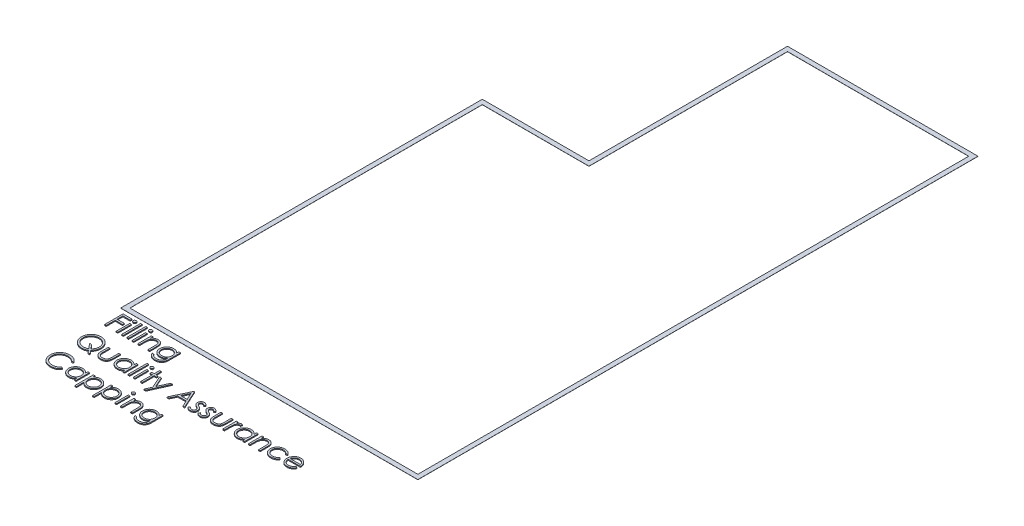
SolidWorks part; units mm, degrees
ref_plane "Front Plane" through (0, 0, 0) normal (0, 0, 1) x (1, 0, 0)
ref_plane "Top Plane" through (0, 0, 0) normal (0, 1, 0) x (1, 0, 0)
ref_plane "Right Plane" through (0, 0, 0) normal (1, 0, 0) x (0, 0, -1)
sketch "Sketch1" plane through (0, 0, 0) normal (0, 1, 0) x (1, 0, 0)
  line L0 (-84.864, 600.662) -> (316.6605, 600.662) construction
  line L1 (316.6605, 600.662) -> (316.6605, -599.338) construction
  line L2 (316.6605, -599.338) -> (-315.3364, -599.338) construction
  line L3 (-315.3364, -599.338) -> (-315.3364, 171.8359) construction
  line L4 (-315.3364, 171.8359) -> (-84.864, 171.8359) construction
  line L5 (-84.864, 171.8359) -> (-84.864, 600.662) construction
  line L6 (-320.3364, 176.8359) -> (-89.864, 176.8359)
  line L7 (-89.864, 176.8359) -> (-89.864, 605.662)
  line L8 (-89.864, 605.662) -> (321.6605, 605.662)
  line L9 (321.6605, 605.662) -> (321.6605, -604.338)
  line L10 (321.6605, -604.338) -> (-320.3364, -604.338)
  line L11 (-320.3364, -604.338) -> (-320.3364, 176.8359)
  line L12 (-310.3364, 166.8359) -> (-79.864, 166.8359)
  line L13 (-79.864, 166.8359) -> (-79.864, 595.662)
  line L14 (-79.864, 595.662) -> (311.6605, 595.662)
  line L15 (311.6605, 595.662) -> (311.6605, -594.338)
  line L16 (311.6605, -594.338) -> (-310.3364, -594.338)
  line L17 (-310.3364, -594.338) -> (-310.3364, 166.8359)
  dimension "D1" = 5
  dimension "D2" = 5
extrude "Boss-Extrude1" add sketch "Sketch1" along normal blind 0.3
sketch "Sketch3" plane through (0, 0, 0) normal (0, 1, 0) x (1, 0, 0)
  line L0 (-310.3364, -654.338) -> (311.6605, -654.338) construction
  line L1 (-310.3364, 166.8359) -> (-310.3364, -594.338) construction
  line L2 (311.6605, -594.338) -> (311.6605, 595.662) construction
  line L3 (-320.3364, -604.338) -> (321.6605, -604.338) construction
  text T0 "Filling\r\nQuality Assurance\r\nCapping" font "Century Gothic" height 40
  dimension "D1" = 50
extrude "Boss-Extrude2" add sketch "Sketch3" along normal blind 2 separate body
